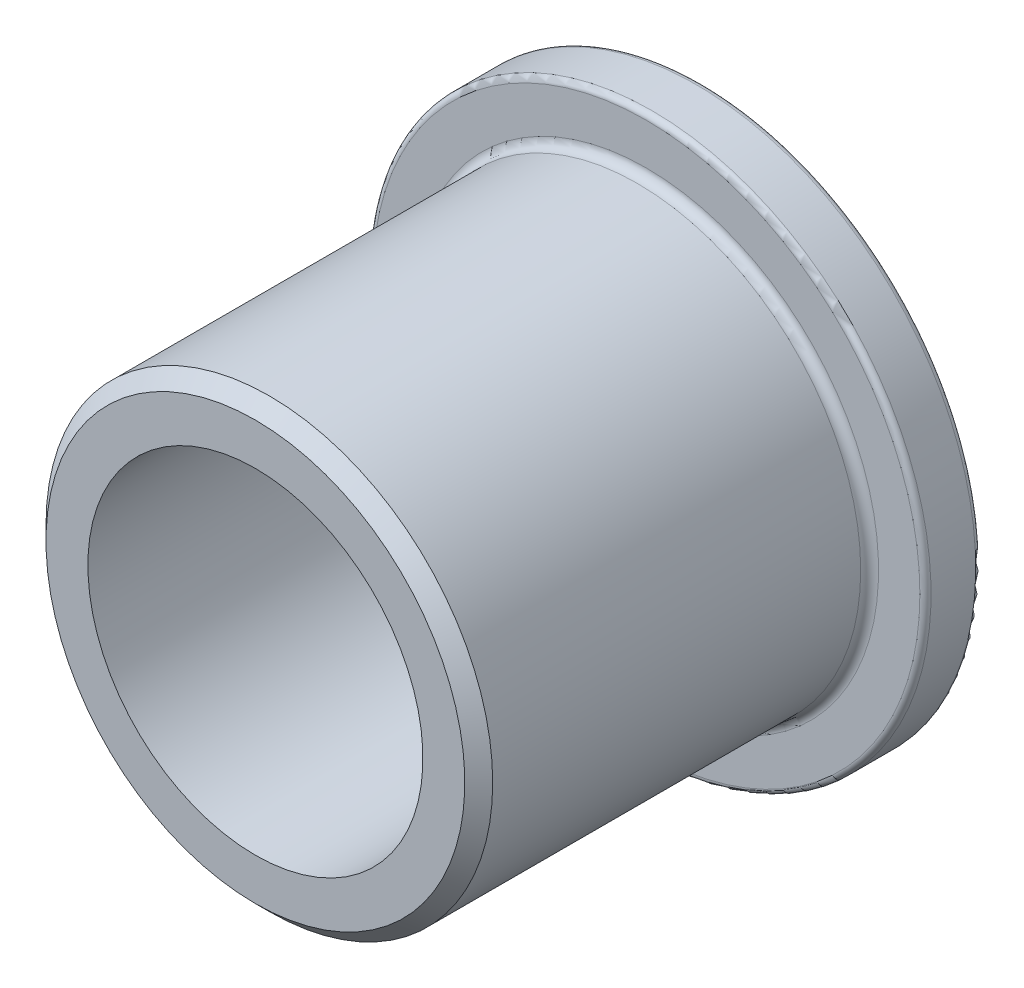
SolidWorks part; units mm, degrees
ref_plane "Front Plane" through (0, 0, 0) normal (0, 0, 1) x (1, 0, 0)
ref_plane "Top Plane" through (0, 0, 0) normal (0, 1, 0) x (1, 0, 0)
ref_plane "Right Plane" through (0, 0, 0) normal (1, 0, 0) x (0, 0, -1)
sketch "Sketch1" plane through (0, 0, 0) normal (1, 0, 0) x (0, 0, -1)
  line L0 (-6.35, 0) -> (6.35, 0) construction
  line L1 (6.35, 7.9375) -> (6.35, -7.9375) construction
  line L2 (-6.35, 6.35) -> (-6.35, -6.35) construction
  line L3 (6.35, 7.9375) -> (4.7625, 7.9375) construction
  line L4 (6.35, -7.9375) -> (4.7625, -7.9375) construction
  point P2 (0, 0)
  point P7 (-6.35, 0)
  point P8 (-6.35, -4.7625)
  point P9 (6.35, 0)
  point P11 (-6.35, 4.7625)
  dimension "Flange OD" = 15.875
  dimension "OD" = 12.7
  dimension "ID" = 9.525
  dimension "Length" = 12.7
  dimension "Flange Thickness" = 1.5875
sketch "Sketch2" plane through (0, 0, 0) normal (0, 0, 1) x (1, 0, 0)
  line L0 (-7.9375, 0) -> (7.9375, 0) construction
  line L1 (0, -7.9375) -> (0, 7.9375) construction
  circle A0 centre (0, 0) radius 4.7625 construction
  circle A1 centre (0, 0) radius 6.35 construction
  circle A2 centre (0, 0) radius 7.9375 construction
  dimension "ID" = 9.525
  dimension "OD" = 12.7
  dimension "Flange OD" = 15.875
sketch "Sketch3" plane through (0, 0, 0) normal (1, 0, 0) x (0, 0, -1)
  line L0 (-6.35, 4.7625) -> (6.35, 4.7625)
  line L1 (6.35, 7.9375) -> (6.35, -7.9375) construction
  line L2 (6.35, 4.7625) -> (6.35, 7.9375)
  line L3 (6.35, 7.9375) -> (4.7625, 7.9375)
  line L4 (4.7625, 7.9375) -> (4.7625, 6.35)
  line L5 (4.7625, 6.35) -> (-6.35, 6.35)
  line L6 (-6.35, 6.35) -> (-6.35, 4.7625)
  line L7 (-6.35, 0) -> (6.35, 0) construction
revolve "Revolve1" add sketch "Sketch3" angle 360 about L7
chamfer "Chamfer1" distance 0.3969 angle 45 1 edges at (0, -6.35, 6.35)
fillet "Fillet1" radius 0.254 1 edges at (0, -6.35, -4.7625)
fillet "Fillet2" radius 0.1588 2 edges at (0, -7.9375, -6.35) (0, -7.9375, -4.7625)
chamfer "Chamfer2" distance 0.4763 angle 45 1 edges at (0, -4.7625, -6.35)
equation "\"D1@Chamfer1\"=((\"OD@Sketch1\"-\"ID@Sketch1\")/2)*.25"
equation "\"D1@Fillet1\"=\"OD@Sketch1\"*.02"
equation "\"D1@Fillet2\"=\"Flange OD@Sketch1\"*.01"
equation "\"D1@Chamfer2\"=\"ID@Sketch1\"*.05"
